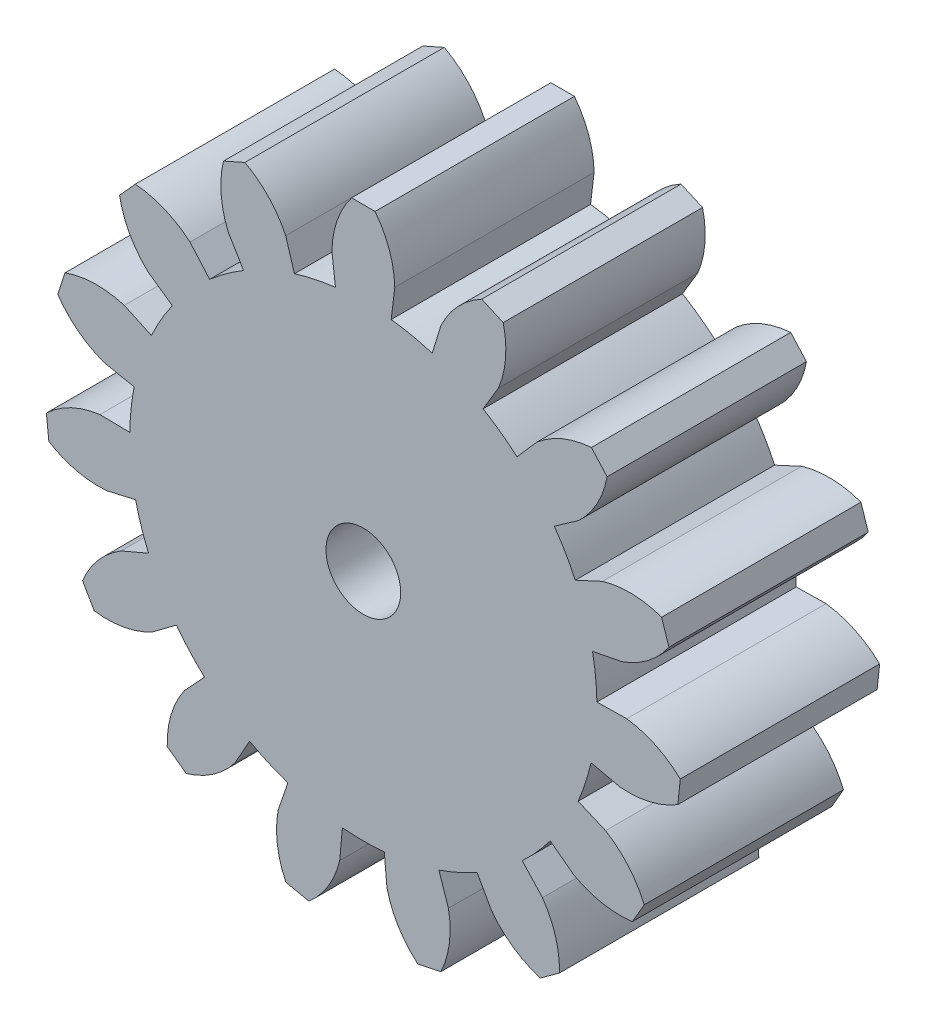
SolidWorks part; units mm, degrees
ref_plane "Front Plane" through (0, 0, 0) normal (0, 0, 1) x (1, 0, 0)
ref_plane "Top Plane" through (0, 0, 0) normal (0, 1, 0) x (1, 0, 0)
ref_plane "Right Plane" through (0, 0, 0) normal (1, 0, 0) x (0, 0, -1)
sketch "Sketch2" plane through (0, 0, 0) normal (0, 0, 1) x (1, 0, 0)
  circle A0 centre (0, 0) radius 9.375
  dimension "D1" = 18.75
extrude "Boss-Extrude1" add sketch "Sketch2" along normal blind 8
sketch "Sketch3" plane through (0, 0, 8) normal (0, 0, 1) x (1, 0, 0)
  line L0 (0, 0) -> (0, 35) construction
  line L1 (0, 0) -> (1.2617, 10.4964)
  line L2 (0, 0) -> (1.1759, 11.1884) construction
  line L3 (0, 0) -> (0.4719, 12.7413) construction
  line L4 (0, 0) -> (-1.2617, 10.4964)
  line L5 (-0.4719, 12.7413) -> (0.4719, 12.7413)
  arc A0 (1.2617, 10.4964) -> (0.4719, 12.7413) centre (-2.5432, 10.4192) ccw
  arc A1 (-1.2617, 10.4964) -> (-0.4719, 12.7413) centre (2.5432, 10.4192) cw
  dimension "D3" = 11.25
  dimension "D5" = 0.9438
  dimension "D1" = 35
  dimension "D2" = 10.572
  dimension "D4" = 12.75
extrude "Boss-Extrude2" add sketch "Sketch3" against normal blind 8
pattern_circular "CirPattern1" count 15 over 360 about axis through (0, 0, 0) along (0, 0, 1) of "Boss-Extrude2"
sketch "Sketch4" plane through (0, 0, 8) normal (0, 0, 1) x (1, 0, 0)
  circle A0 centre (0, 0) radius 1.5
  dimension "D1" = 3
extrude "Cut-Extrude1" cut sketch "Sketch4" against normal blind 8
